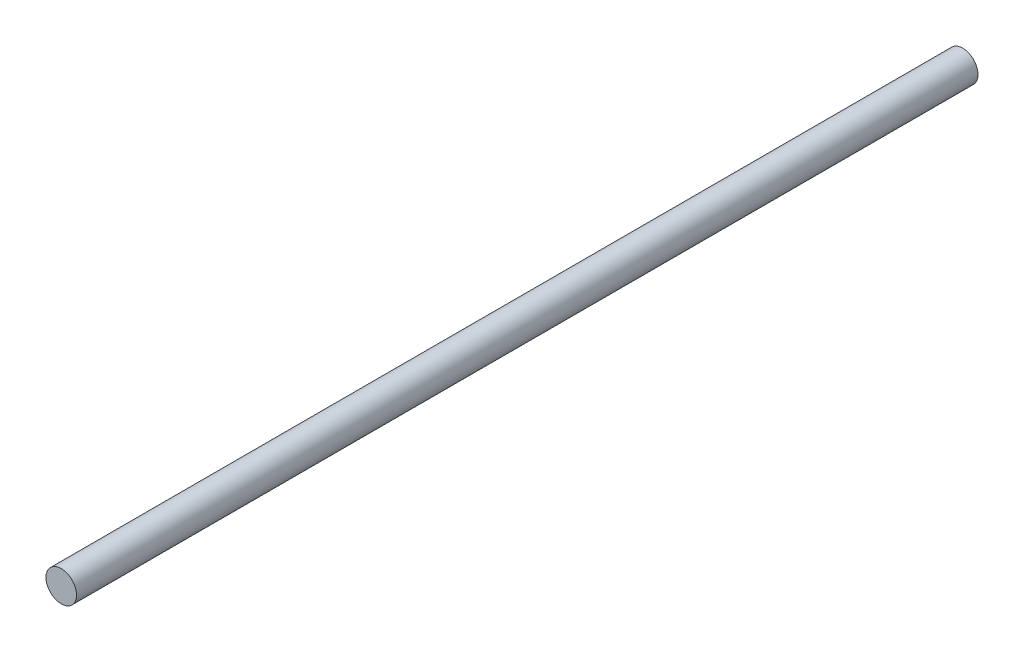
SolidWorks part; units mm, degrees
ref_plane "Front Plane" through (0, 0, 0) normal (0, 0, 1) x (1, 0, 0)
ref_plane "Top Plane" through (0, 0, 0) normal (0, 1, 0) x (1, 0, 0)
ref_plane "Right Plane" through (0, 0, 0) normal (1, 0, 0) x (0, 0, -1)
sketch "Sketch1" plane through (0, 0, 0) normal (0, 0, 1) x (1, 0, 0)
  circle A0 centre (11.5, -184.6746) radius 5
  circle A1 centre (11.5, -184.6746) radius 5 construction
  dimension "D1" = 10
extrude "Boss-Extrude1" add sketch "Sketch1" along normal blind 25 and the other way blind 270
